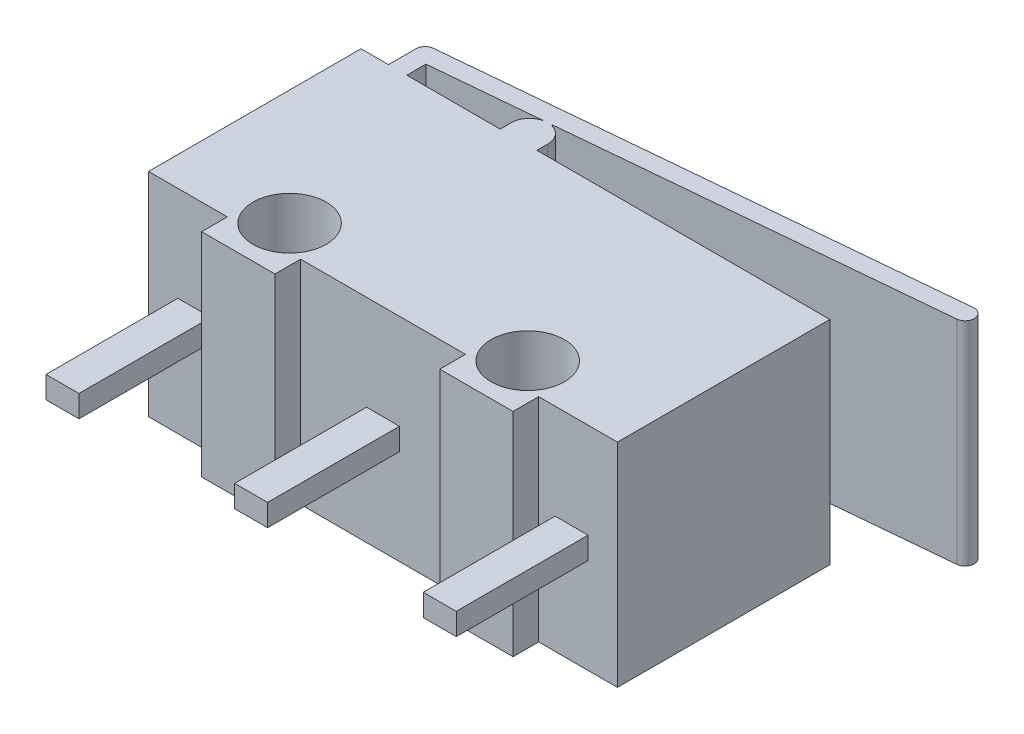
SolidWorks part; units mm, degrees
ref_plane "Front Plane" through (0, 0, 0) normal (0, 0, 1) x (1, 0, 0)
ref_plane "Top Plane" through (0, 0, 0) normal (0, 1, 0) x (1, 0, 0)
ref_plane "Right Plane" through (0, 0, 0) normal (1, 0, 0) x (0, 0, -1)
sketch "Sketch1" plane through (0, 0, 0) normal (0, 1, 0) x (1, 0, 0)
  line L0 (0, 0) -> (0, -2.9) construction
  line L1 (-6.4, -2.9) -> (6.4, -2.9)
  line L2 (-6.4, -2.9) -> (-6.4, 2.9)
  line L3 (-6.4, 2.9) -> (6.4, 2.9)
  line L4 (6.4, -2.9) -> (6.4, 2.9)
  line L5 (-6.4, -2.9) -> (6.4, 2.9) construction
  line L6 (-6.4, 2.9) -> (6.4, -2.9) construction
  line L7 (-3.25, -2.2) -> (3.25, -2.2) construction
  line L8 (4.25, -2.9) -> (2.25, -2.9)
  line L9 (-4.25, -3.6) -> (-2.25, -3.6)
  line L10 (-4.25, -3.6) -> (-4.25, -2.9)
  line L11 (-4.25, -2.9) -> (-2.25, -2.9)
  line L12 (-2.25, -3.6) -> (-2.25, -2.9)
  line L13 (-4.25, -3.6) -> (-2.25, -2.9) construction
  line L14 (-4.25, -2.9) -> (-2.25, -3.6) construction
  line L15 (2.25, -3.6) -> (2.25, -2.9)
  line L16 (4.25, -3.6) -> (2.25, -3.6)
  line L17 (4.25, -3.6) -> (4.25, -2.9)
  line L18 (-2.1, 2.9) -> (-2.1, 3.2) construction
  line L19 (-2.6, 2.9) -> (-2.6, 3.2)
  line L20 (-1.6, 2.9) -> (-1.6, 3.2)
  line L21 (-5.4, 3.65) -> (8.1, 4.8902) construction
  line L22 (-5.65, 3.65) -> (-5.15, 3.65)
  line L23 (-5.65, 3.65) -> (-5.65, 2.9)
  line L24 (-5.65, 2.9) -> (-5.15, 2.9)
  line L25 (-5.15, 3.65) -> (-5.15, 2.9)
  line L26 (-5.65, 3.65) -> (-5.15, 2.9) construction
  line L27 (-5.65, 2.9) -> (-5.15, 3.65) construction
  line L28 (-5.4229, 3.899) -> (8.0771, 5.1391)
  line L29 (-5.3771, 3.401) -> (8.1229, 4.6412)
  line L31 (-2.2189, 3.6209) -> (-1.9811, 3.6209)
  line L32 (-2.2189, 3.6209) -> (-2.2189, 3.7833)
  line L33 (-2.2189, 3.7833) -> (-1.9811, 3.7833)
  line L34 (-1.9811, 3.6209) -> (-1.9811, 3.7833)
  line L35 (-2.2189, 3.6209) -> (-1.9811, 3.7833) construction
  line L36 (-2.2189, 3.7833) -> (-1.9811, 3.6209) construction
  circle A0 centre (-3.25, -2.2) radius 1
  circle A1 centre (3.25, -2.2) radius 1
  arc A2 (-2.6, 2.9) -> (-1.6, 2.9) centre (-2.1, 2.9) ccw
  arc A3 (-1.6, 3.2) -> (-2.6, 3.2) centre (-2.1, 3.2) ccw
  arc A4 (-5.4229, 3.899) -> (-5.3771, 3.401) centre (-5.4, 3.65) ccw
  arc A5 (8.1229, 4.6412) -> (8.0771, 5.1391) centre (8.1, 4.8902) ccw
  point P0 (0, 0)
  point P11 (0, -2.2)
  point P13 (-3.25, -3.25)
  point P22 (-2.1, 3.05)
  point P29 (-2.1, 3.7)
  point P30 (-5.4, 3.275)
  point P35 (-5.65, 3.275)
  point P38 (1.35, 4.2701)
  point P44 (-2.1, 3.7021)
  dimension "D3" = 2
  dimension "D4" = 2
  dimension "D1" = 12.8
  dimension "D2" = 5.8
  dimension "D5" = 6.5
  dimension "D6" = 5.1
  dimension "D7" = 6.5
  dimension "D8" = 1
  dimension "D9" = 4.3
  dimension "D10" = 1
  dimension "D11" = 7.3
  dimension "D12" = 0.75
  dimension "D13" = 0.5
  dimension "D14" = 0.75
  dimension "D15" = 13.5
extrude "Boss-Extrude1" add sketch "Sketch1" along normal blind 5.8 contours A2 L3 L2 L1 A0 A1 L4 | A0 L1 L10 L9 L12 | A1 L1 L15 L16 L17 | L3 A2 | L20 A3 L19 L3 | L25 L22 L23 L3 | L22 A4 L29 L25 | L29 A5 L28 A4 L22 L25 L32 L33 L34 | L34 A3 L32 L31 | A3 L34 L29 | A3 L29 L32 | L29 L34 L33 L32
sketch "Sketch3" plane through (0, 0, 2.9) normal (0, 0, 1) x (1, 0, 0)
  line L0 (-5.15, 2.9) -> (5.15, 2.9) construction
  line L1 (-6.4, 5.8) -> (-6.4, 0) construction
  line L3 (-5.6, 2.6) -> (-4.7, 2.6)
  line L4 (-5.6, 2.6) -> (-5.6, 3.2)
  line L5 (-5.6, 3.2) -> (-4.7, 3.2)
  line L6 (-4.7, 2.6) -> (-4.7, 3.2)
  line L7 (-5.6, 2.6) -> (-4.7, 3.2) construction
  line L8 (-5.6, 3.2) -> (-4.7, 2.6) construction
  line L9 (-0.45, 2.6) -> (0.45, 2.6)
  line L10 (-0.45, 2.6) -> (-0.45, 3.2)
  line L11 (-0.45, 3.2) -> (0.45, 3.2)
  line L12 (0.45, 2.6) -> (0.45, 3.2)
  line L13 (-0.45, 2.6) -> (0.45, 3.2) construction
  line L14 (-0.45, 3.2) -> (0.45, 2.6) construction
  line L15 (5.6, 2.6) -> (4.7, 2.6)
  line L16 (5.6, 2.6) -> (5.6, 3.2)
  line L17 (5.6, 3.2) -> (4.7, 3.2)
  line L18 (4.7, 2.6) -> (4.7, 3.2)
  line L19 (5.6, 2.6) -> (4.7, 3.2) construction
  line L20 (5.6, 3.2) -> (4.7, 2.6) construction
  point P0 (-6.4, 2.9)
  point P3 (0, 2.9)
  point P4 (0, 2.9)
  point P20 (-1.5372, 3.2)
  point P21 (0, 2.9)
  point P22 (0, 0)
  point P23 (0, 0)
  dimension "D1" = 10.3
  dimension "D2" = 0.6
  dimension "D3" = 0.9
extrude "Boss-Extrude2" add sketch "Sketch3" along normal blind 3.6
